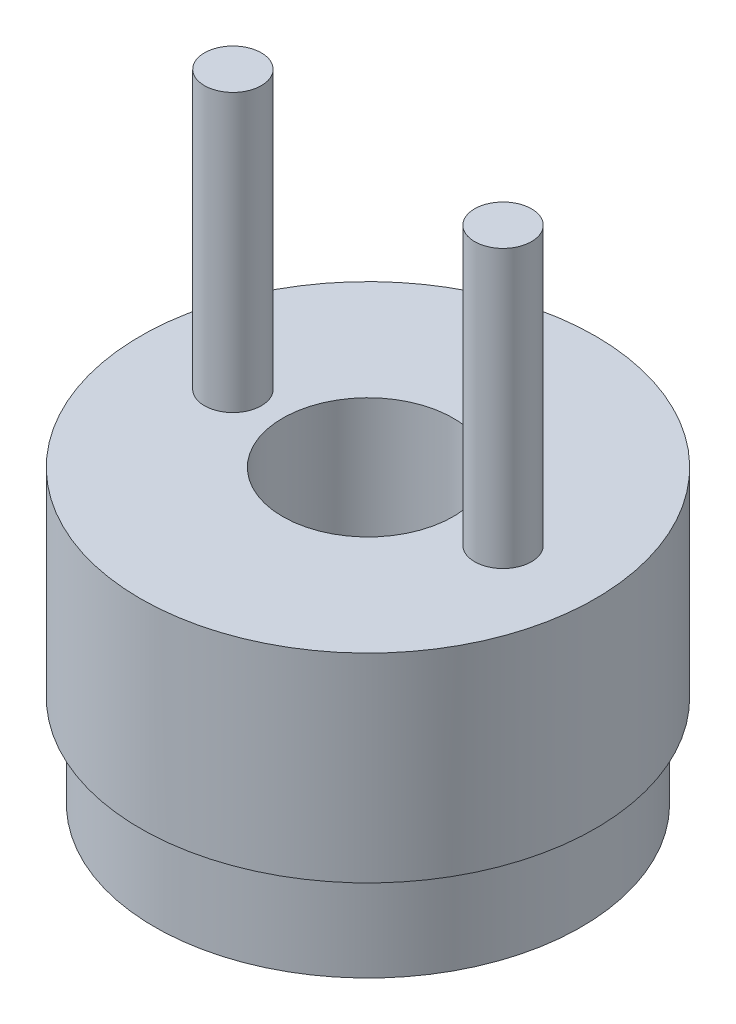
SolidWorks part; units mm, degrees
ref_plane "Front Plane" through (0, 0, 0) normal (0, 0, 1) x (1, 0, 0)
ref_plane "Top Plane" through (0, 0, 0) normal (0, 1, 0) x (1, 0, 0)
ref_plane "Right Plane" through (0, 0, 0) normal (1, 0, 0) x (0, 0, -1)
sketch "Sketch1" plane through (0, 0, 0) normal (0, 1, 0) x (1, 0, 0)
  circle A0 centre (0, 0) radius 16
extrude "Boss-Extrude1" add sketch "Sketch1" along normal blind 40
sketch "Sketch2" plane through (0, 40, 0) normal (0, 1, 0) x (1, 0, 0)
  circle A0 centre (0, 0) radius 6
extrude "Cut-Extrude1" cut sketch "Sketch2" against normal through all
ref_plane "Plane1" through (0, 0, 0) normal (0, -1, 0) x (-1, 0, 0)
sketch "Sketch4" plane through (0, 0, 0) normal (0, -1, 0) x (-1, 0, 0)
  circle A0 centre (0, 0) radius 20
  circle A1 centre (0, 0) radius 15
extrude "Cut-Extrude2" cut sketch "Sketch4" against normal blind 26
sketch "Sketch5" plane through (0, 0, 0) normal (0, -1, 0) x (1, 0, 0)
  circle A0 centre (0, 0) radius 15
extrude "Cut-Extrude3" cut sketch "Sketch5" against normal blind 19.5
sketch "Sketch3" plane through (0, 19.5, 0) normal (0, 1, 0) x (1, 0, 0)
  line L0 (0, 0) -> (21.5142, 0) construction
  line L1 (0, 0) -> (0, 12.4817) construction
  circle A0 centre (-9.5, 0) radius 2
  circle A1 centre (9.5, 0) radius 2
  dimension "D1" = 9.5
extrude "Boss-Extrude2" add sketch "Sketch3" along normal blind 40 separate body
sketch "Sketch7" plane through (0, 0, 0) normal (0, -1, 0) x (-1, 0, 0)
  circle A0 centre (9.5, 0) radius 2
  circle A1 centre (-9.5, 0) radius 2
extrude "Cut-Extrude5" cut sketch "Sketch7" against normal through all
